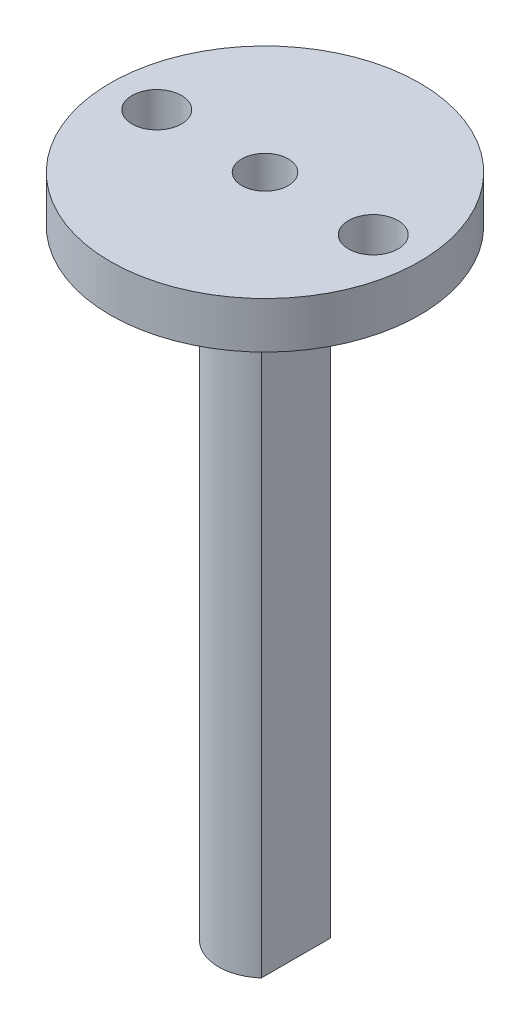
SolidWorks part; units mm, degrees
material "Custom Plastic"
ref_plane "Front Plane" through (0, 0, 0) normal (0, 0, 1) x (1, 0, 0)
ref_plane "Top Plane" through (0, 0, 0) normal (0, 1, 0) x (1, 0, 0)
ref_plane "Right Plane" through (0, 0, 0) normal (1, 0, 0) x (0, 0, -1)
sketch "Sketch1" plane through (0, 0, 0) normal (0, 1, 0) x (1, 0, 0)
  line L0 (0, 0) -> (3, 0) construction
  line L1 (2, 2.2361) -> (2, -2.2361)
  arc A0 (2, 2.2361) -> (2, -2.2361) centre (0, 0) ccw
  circle A1 centre (0, 0) radius 1.5
  dimension "D1" = 6
  dimension "D3" = 3
  dimension "D2" = 2
extrude "Boss-Extrude1" add sketch "Sketch1" along normal blind 40
sketch "Sketch2" plane through (0, 40, 0) normal (0, 1, 0) x (1, 0, 0)
  line L0 (-7, 0) -> (7, 0) construction
  circle A0 centre (0, 0) radius 10
  circle A1 centre (0, 0) radius 7 construction
  circle A2 centre (-7, 0) radius 1.6
  circle A3 centre (7, 0) radius 1.6
  circle A4 centre (0, 0) radius 1.5 construction
  circle A5 centre (0, 0) radius 1.5
  dimension "D1" = 20
  dimension "D2" = 14
  dimension "D3" = 1.6
  dimension "D4" = 3.2
extrude "Boss-Extrude2" add sketch "Sketch2" along normal blind 3
sketch "Sketch3" plane through (0, 0, 0) normal (0, -1, 0) x (1, 0, 0)
  circle A0 centre (0, 0) radius 1.5
